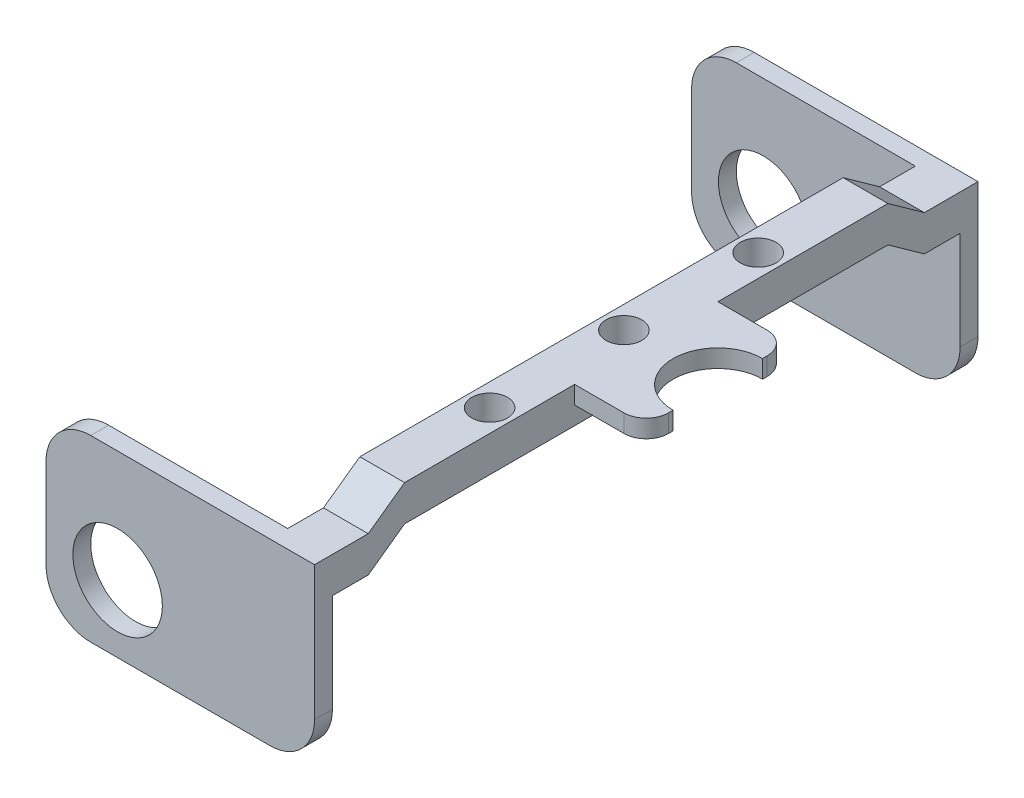
SolidWorks part; units mm, degrees
ref_plane "Front Plane" through (0, 0, 0) normal (0, 0, 1) x (1, 0, 0)
ref_plane "Top Plane" through (0, 0, 0) normal (0, 1, 0) x (1, 0, 0)
ref_plane "Right Plane" through (0, 0, 0) normal (1, 0, 0) x (0, 0, -1)
sketch "Sketch1" plane through (0, 0, 0) normal (0, 1, 0) x (1, 0, 0)
  line L1 (0, 27) -> (-5, 27)
  line L2 (0, 27) -> (0, -27)
  line L3 (0, -27) -> (-5, -27)
  line L4 (-5, 27) -> (-5, -27)
  dimension "D1" = 54
  dimension "D2" = 5
  dimension "D3" = 27
extrude "Boss-Extrude1" add sketch "Sketch1" along normal blind 4
sketch "Sketch3" plane through (0, 0, 0) normal (0, 1, 0) x (1, 0, 0)
  line L0 (0, -27) -> (0, 27) construction
  line L1 (0, -8) -> (16, -8)
  line L2 (0, -8) -> (0, 8)
  line L3 (0, 8) -> (16, 8)
  line L4 (16, -8) -> (16, 8)
  dimension "D1" = 16
  dimension "D2" = 16
  dimension "D3" = 8
extrude "Boss-Extrude2" add sketch "Sketch3" along normal blind 4
sketch "Sketch4" plane through (0, 4, 0) normal (0, 1, 0) x (1, 0, 0)
  circle A0 centre (8, 0) radius 5
  dimension "D1" = 10
sketch "Sketch5" plane through (0, 0, 0) normal (1, 0, 0) x (0, 0, -1)
  line L0 (-27, 4) -> (-31.0631, 1.0861)
  dimension "D1" = 5
sketch "Sketch6" plane through (0, 0, 27) normal (0, 0, 1) x (1, 0, 0)
  line L1 (-5, 4) -> (0, 4)
  line L2 (-5, 4) -> (-5, 0)
  line L3 (-5, 0) -> (0, 0)
  line L4 (0, 4) -> (0, 0)
extrude "Boss-Extrude5" add sketch "Sketch6" along direction (0, -0.5828, 0.8126) on the side of the normal blind 5
mirror "Mirror1" about plane through (0, 0, 0) normal (0, 0, 1) of "Boss-Extrude5"
sketch "Sketch7" plane through (0, 4, 0) normal (0, 1, 0) x (1, 0, 0)
  circle A0 centre (-2.5, 0) radius 2
  circle A1 centre (-2.5, 15) radius 2
  circle A2 centre (-2.5, -15) radius 2
  dimension "D1" = 4
  dimension "D2" = 4
  dimension "D3" = 15
  dimension "D5" = 4
  dimension "D4" = 15
sketch "Sketch10" plane through (0, 0, 31.0631) normal (0, 0, 1) x (1, 0, 0)
  line L1 (0, 1.0861) -> (-30, 1.0861)
  line L2 (0, 1.0861) -> (0, -18.9139)
  line L3 (0, -18.9139) -> (-30, -18.9139)
  line L4 (-30, 1.0861) -> (-30, -18.9139)
  dimension "D1" = 20
  dimension "D2" = 30
extrude "Boss-Extrude9" add sketch "Sketch10" along normal blind 6
extrude "Cut-Extrude2" cut sketch "Sketch7" against normal up to next
extrude "Cut-Extrude3" cut sketch "Sketch4" against normal up to next
sketch "Sketch12" plane through (0, 0, 0) normal (0, -1, 0) x (1, 0, 0)
  line L1 (16, 8) -> (0, 8)
  line L2 (16, 8) -> (16, -8)
  line L3 (16, -8) -> (0, -8)
  line L4 (0, 8) -> (0, -8)
extrude "Cut-Extrude4" cut sketch "Sketch12" against normal blind 2
sketch "Sketch13" plane through (0, 0, 31.0631) normal (0, 0, -1) x (-1, 0, 0)
  line L0 (30, 1.0861) -> (5, 1.0861)
  line L1 (5, 1.0861) -> (5, -2.9139)
  line L2 (5, -2.9139) -> (0, -2.9139)
  line L3 (0, -2.9139) -> (0, -18.9139)
  line L4 (0, -18.9139) -> (30, -18.9139)
  line L5 (30, -18.9139) -> (30, 1.0861)
extrude "Cut-Extrude5" cut sketch "Sketch13" against normal blind 4
sketch "Sketch14" plane through (0, 0, 37.0631) normal (0, 0, 1) x (1, 0, 0)
  line L0 (-30, 1.0861) -> (-30, -18.9139) construction
  line L1 (-30, -18.9139) -> (0, -18.9139) construction
  circle A0 centre (-22, -11.4139) radius 5
  dimension "D1" = 10
  dimension "D2" = 8
  dimension "D3" = 7.5
extrude "Cut-Extrude6" cut sketch "Sketch14" against normal up to next
fillet "Fillet1" radius 5 3 edges at (-30, -18.9139, 36.0631) (-30, 1.0861, 36.0631) (0, -18.9139, 36.0631)
mirror "Mirror2" about plane through (0, 0, 0) normal (0, 0, 1) of "Boss-Extrude9", "Cut-Extrude5", "Cut-Extrude6", "Fillet1"
sketch "Sketch15" plane through (0, 4, 0) normal (0, 1, 0) x (1, 0, 0)
  line L0 (8, 5) -> (8, 8)
  line L1 (16, 8) -> (0, 8) construction
  line L2 (8, 8) -> (16, 8)
  line L3 (16, 8) -> (16, -8)
  line L4 (16, -8) -> (8, -8)
  line L5 (0, -8) -> (16, -8) construction
  line L6 (8, -8) -> (8, -5)
  arc A0 (8, -5) -> (8, 5) centre (8, 0) ccw
  circle A1 centre (8, 0) radius 5 construction
extrude "Cut-Extrude7" cut sketch "Sketch15" against normal up to next
fillet "Fillet2" radius 2.5 2 edges at (8, 3, 8) (8, 3, -8)
